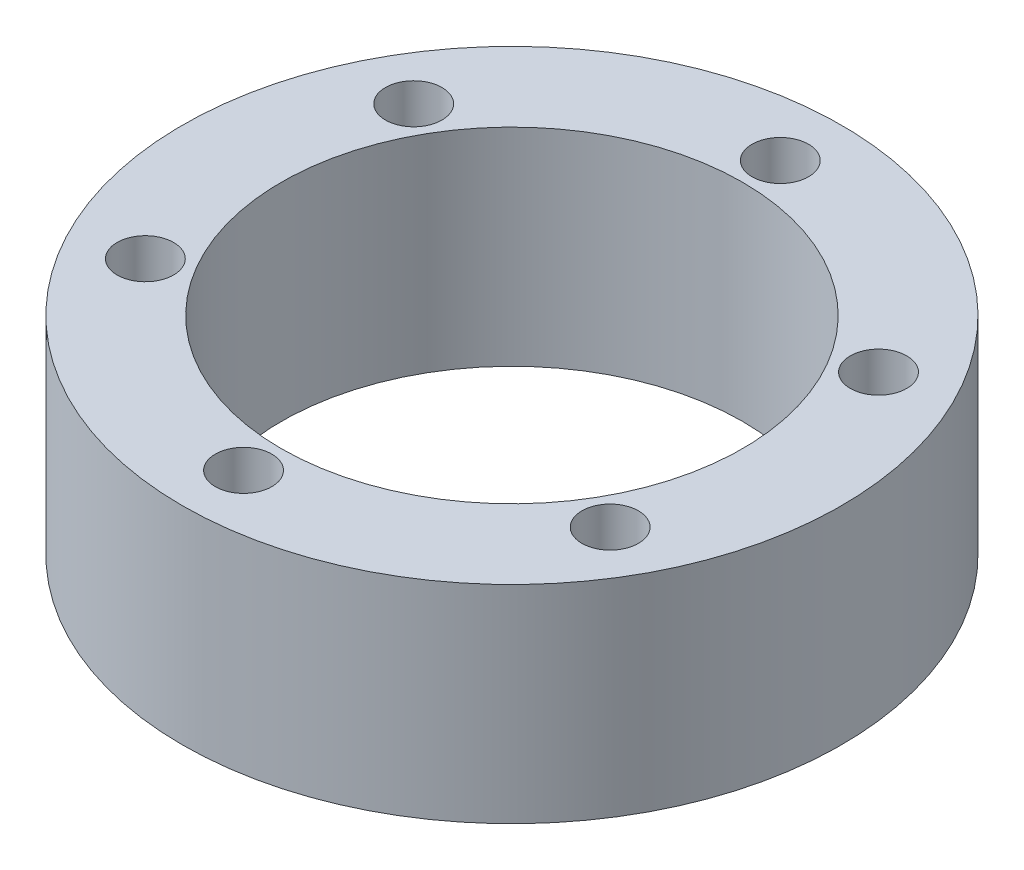
SolidWorks part; units mm, degrees
ref_plane "Front Plane" through (0, 0, 0) normal (0, 0, 1) x (1, 0, 0)
ref_plane "Top Plane" through (0, 0, 0) normal (0, 1, 0) x (1, 0, 0)
ref_plane "Right Plane" through (0, 0, 0) normal (1, 0, 0) x (0, 0, -1)
sketch "Sketch1" plane through (0, 0, 0) normal (0, 1, 0) x (1, 0, 0)
  line L0 (0, 28.5) -> (6.6261, 28.5) construction
  line L1 (0, 28.5) -> (0, 22.9557) construction
  circle A0 centre (0, 0) radius 24.5
  circle A1 centre (0, 0) radius 35
  circle A2 centre (0, 0) radius 28.5 construction
  circle A3 centre (0, 28.5) radius 3
  arc A4 (3.9901, 28.2193) -> (0, 24.5) centre (0, 28.5) ccw construction
  circle A5 centre (24.6817, 14.25) radius 3
  circle A6 centre (24.6817, -14.25) radius 3
  circle A7 centre (0, -28.5) radius 3
  circle A8 centre (-24.6817, -14.25) radius 3
  circle A9 centre (-24.6817, 14.25) radius 3
  point P23 (0, 0)
  dimension "D1" = 70
  dimension "D2" = 49
  dimension "D3" = 57
  dimension "D4" = 6
  dimension "D5" = 1
  dimension "D6" = 6
extrude "Boss-Extrude1" add sketch "Sketch1" along normal blind 22
